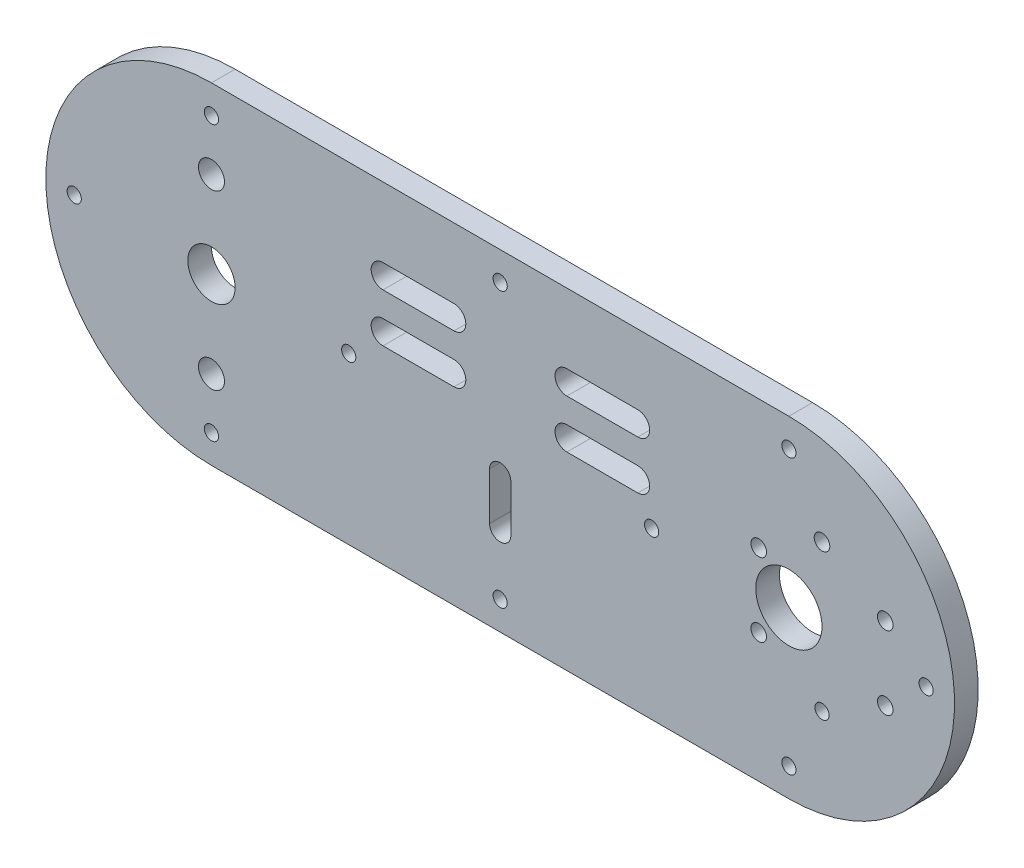
SolidWorks part; units mm, degrees
ref_plane "Front Plane" through (0, 0, 0) normal (0, 0, 1) x (1, 0, 0)
ref_plane "Top Plane" through (0, 0, 0) normal (0, 1, 0) x (1, 0, 0)
ref_plane "Right Plane" through (0, 0, 0) normal (1, 0, 0) x (0, 0, -1)
sketch "Sketch1" plane through (0, 0, 0) normal (0, 0, 1) x (1, 0, 0)
  line L0 (61, 0) -> (-61, 0) construction
  line L1 (-61, 5) -> (-24.76, 5) construction
  line L2 (61, -35) -> (-61, -35)
  line L3 (61, 35) -> (-61, 35)
  line L4 (0, -6.25) -> (0, -16.25) construction
  line L6 (2.25, -6.25) -> (2.25, -16.25)
  line L7 (-2.25, -6.25) -> (-2.25, -16.25)
  line L12 (-9.76, 7.5) -> (14.09, 7.5) construction
  line L13 (-24.76, 7.5) -> (-9.76, 7.5) construction
  line L14 (-24.76, 17.74) -> (-9.76, 17.74) construction
  line L15 (-24.76, 10) -> (-9.76, 10)
  line L16 (-24.76, 5) -> (-9.76, 5)
  line L17 (14.09, 7.5) -> (29.09, 7.5) construction
  line L18 (-24.76, 20.24) -> (-9.76, 20.24)
  line L19 (-24.76, 15.24) -> (-9.76, 15.24)
  line L21 (14.09, 10) -> (29.09, 10)
  line L22 (14.09, 5) -> (29.09, 5)
  line L23 (14.09, 17.74) -> (29.09, 17.74) construction
  line L25 (14.09, 20.24) -> (29.09, 20.24)
  line L26 (14.09, 15.24) -> (29.09, 15.24)
  arc A0 (61, -35) -> (61, 35) centre (61, 0) ccw
  arc A1 (-61, 35) -> (-61, -35) centre (-61, 0) ccw
  circle A2 centre (61, 0) radius 7
  circle A3 centre (-61, 0) radius 5
  circle A4 centre (-61, -29) radius 1.5
  circle A5 centre (-61, 29) radius 1.5
  circle A6 centre (61, 29) radius 1.5
  circle A7 centre (61, -29) radius 1.5
  circle A8 centre (0, -29) radius 1.5
  circle A9 centre (0, 29) radius 1.5
  circle A10 centre (-61, 18.25) radius 2.75
  circle A11 centre (-61, -18.25) radius 2.75
  circle A12 centre (-90, 0) radius 1.5
  circle A13 centre (-32, 0) radius 1.5
  arc A14 (2.25, -6.25) -> (-2.25, -6.25) centre (0, -6.25) ccw
  arc A15 (-2.25, -16.25) -> (2.25, -16.25) centre (0, -16.25) ccw
  circle A16 centre (90, 0) radius 1.5
  circle A17 centre (32, 0) radius 1.5
  circle A19 centre (68, -15.5) radius 1.5
  circle A20 centre (68, 15.5) radius 1.65
  circle A21 centre (54.6305, 7.7559) radius 1.65
  circle A22 centre (54.6305, -7.7559) radius 1.65
  circle A23 centre (81.3695, -7.7559) radius 1.65
  circle A24 centre (81.3695, 7.7559) radius 1.65
  arc A26 (-24.76, 10) -> (-24.76, 5) centre (-24.76, 7.5) ccw
  arc A27 (-9.76, 5) -> (-9.76, 10) centre (-9.76, 7.5) ccw
  arc A28 (-24.76, 20.24) -> (-24.76, 15.24) centre (-24.76, 17.74) ccw
  arc A29 (-9.76, 15.24) -> (-9.76, 20.24) centre (-9.76, 17.74) ccw
  arc A30 (14.09, 10) -> (14.09, 5) centre (14.09, 7.5) ccw
  arc A31 (29.09, 5) -> (29.09, 10) centre (29.09, 7.5) ccw
  arc A32 (14.09, 20.24) -> (14.09, 15.24) centre (14.09, 17.74) ccw
  arc A33 (29.09, 15.24) -> (29.09, 20.24) centre (29.09, 17.74) ccw
  point P5 (0, 0)
  point P27 (-61, 0)
  point P32 (-61, 0)
  point P39 (0, -11.25)
  point P63 (-17.26, 7.5)
  point P71 (-17.26, 17.74)
  point P78 (21.59, 7.5)
  point P86 (21.59, 17.74)
  dimension "D1" = 14
  dimension "D2" = 10
  dimension "D3" = 6
  dimension "D4" = 3
  dimension "D5" = 6
  dimension "D6" = 3
  dimension "D8" = 3
  dimension "D9" = 3
  dimension "D12" = 3
  dimension "D13" = 3
  dimension "D14" = 70
  dimension "D15" = 5.5
  dimension "D16" = 5.5
  dimension "D19" = 3
  dimension "D20" = 3
  dimension "D24" = 29
  dimension "D25" = 3
  dimension "D26" = 3
  dimension "D27" = 7
  dimension "D28" = 3.3
  dimension "D29" = 3
  dimension "D30" = 3.3
  dimension "D31" = 3.3
  dimension "D32" = 3.3
  dimension "D33" = 3.3
  dimension "D34" = 7
  dimension "D7" = 122
  dimension "D10" = 6
  dimension "D11" = 6
  dimension "D17" = 36.5
  dimension "D18" = 58
  dimension "D21" = 4.5
  dimension "D22" = 10
  dimension "D23" = 29
  dimension "D35" = 36.24
  dimension "D36" = 15
  dimension "D37" = 5
  dimension "D38" = 5.24
  dimension "D39" = 5.24
  dimension "D40" = 23.85
  dimension "D41" = 5
  dimension "D42" = 15
  dimension "D43" = 15
  dimension "D44" = 5
  dimension "D45" = 6
  dimension "D46" = 6
extrude "Boss-Extrude1" add sketch "Sketch1" along normal blind 5
